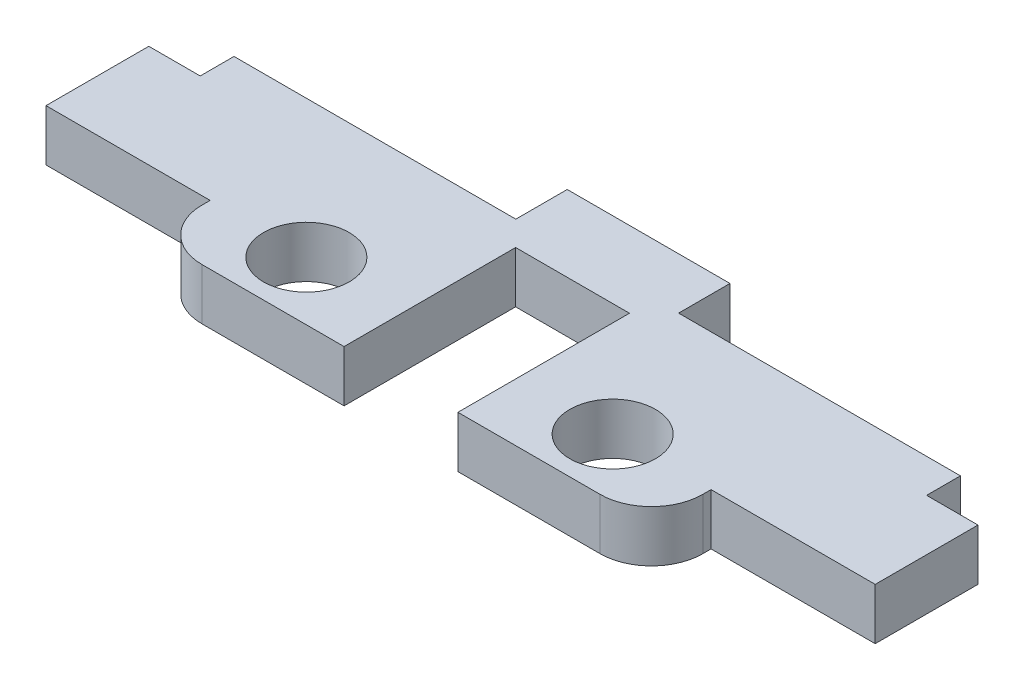
SolidWorks part; units mm, degrees
ref_plane "Front Plane" through (0, 0, 0) normal (0, 0, 1) x (1, 0, 0)
ref_plane "Top Plane" through (0, 0, 0) normal (0, 1, 0) x (1, 0, 0)
ref_plane "Right Plane" through (0, 0, 0) normal (1, 0, 0) x (0, 0, -1)
sketch "Sketch1" plane through (0, 0, 0) normal (0, 1, 0) x (1, 0, 0)
  line L3 (17.6158, 6.4057) -> (17.6158, 7.3645)
  line L4 (17.6158, 7.3645) -> (-1.5453, 7.3645)
  line L5 (-1.5453, 7.3645) -> (-1.5453, 19.3645)
  line L6 (37.3518, 29.3111) -> (56.3518, 29.3111)
  line L7 (95.2489, 7.3645) -> (95.2489, 19.3645)
  line L8 (95.2489, 7.3645) -> (76.0878, 7.3645)
  line L9 (76.0878, 7.3645) -> (76.0878, 6.4057)
  line L14 (70.0878, 0.4057) -> (53.4968, 0.4057)
  line L16 (-1.5453, 19.3645) -> (4.4547, 19.3645)
  line L17 (28.9745, 7.2378) -> (64.7291, 7.2378) construction
  line L18 (40.2069, 0.4057) -> (23.6158, 0.4057)
  line L19 (4.4547, 19.3645) -> (4.4547, 23.3111)
  line L20 (40.2069, 0.4057) -> (40.2069, 20.4324)
  line L21 (40.2069, 20.4324) -> (53.4968, 20.4324)
  line L22 (53.4968, 0.4057) -> (53.4968, 20.4324)
  line L23 (95.2489, 19.3645) -> (89.2489, 19.3645)
  line L24 (89.2489, 19.3645) -> (89.2489, 23.3111)
  line L25 (37.3518, 29.3111) -> (37.3518, 23.3111)
  line L26 (4.4547, 19.3645) -> (89.2489, 19.3645) construction
  line L27 (56.3518, 29.3111) -> (56.3518, 23.3111)
  line L28 (56.3518, 23.3111) -> (89.2489, 23.3111)
  line L30 (37.3518, 23.3111) -> (4.4547, 23.3111)
  circle A0 centre (28.9745, 7.2378) radius 5
  circle A1 centre (64.7291, 7.2378) radius 5
  arc A2 (76.0878, 6.4057) -> (70.0878, 0.4057) centre (70.0878, 6.4057) cw
  arc A3 (17.6158, 6.4057) -> (23.6158, 0.4057) centre (23.6158, 6.4057) ccw
  point P17 (46.8518, 29.3111)
  point P24 (46.8518, 7.2378)
  point P25 (46.8518, 20.4324)
  dimension "D1" = 6
extrude "Boss-Extrude1" add sketch "Sketch1" along normal blind 6
